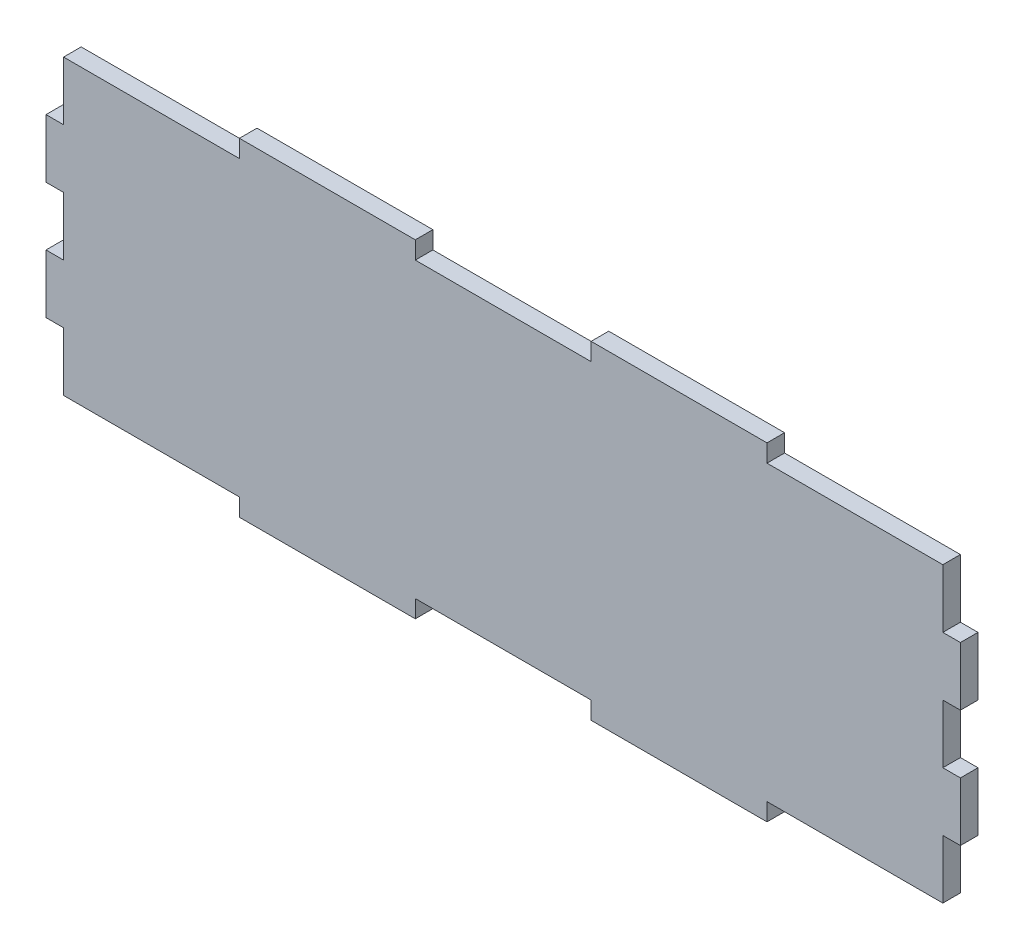
SolidWorks part; units mm, degrees
material "Pinho"
ref_plane "Plano frontal" through (0, 0, 0) normal (0, 0, 1) x (1, 0, 0)
ref_plane "Plano superior" through (0, 0, 0) normal (0, 1, 0) x (1, 0, 0)
ref_plane "Plano direito" through (0, 0, 0) normal (1, 0, 0) x (0, 0, -1)
sketch "Esboço1" plane through (0, 0, 0) normal (0, 0, 1) x (1, 0, 0)
  line L51 (-90, 33) -> (-90, 30)
  line L53 (-60, 30) -> (-60, 33)
  line L55 (-30, 33) -> (-30, 30)
  line L57 (0, 30) -> (0, 33)
  line L59 (-90, 33) -> (-60, 33)
  line L60 (-30, 33) -> (0, 33)
  line L62 (-60, 30) -> (-30, 30)
  line L65 (-90, -20) -> (-90, -23)
  line L66 (-90, -23) -> (-60, -23)
  line L67 (-60, -23) -> (-60, -20)
  line L68 (-60, -20) -> (-30, -20)
  line L69 (-30, -20) -> (-30, -23)
  line L82 (-90, -20) -> (-120, -20)
  line L83 (-120, -20) -> (-120, -10)
  line L84 (-120, -10) -> (-123, -10)
  line L85 (-123, -10) -> (-123, 0)
  line L86 (-123, 0) -> (-120, 0)
  line L87 (-120, 0) -> (-120, 10)
  line L88 (-120, 10) -> (-123, 10)
  line L89 (-123, 10) -> (-123, 20)
  line L90 (-123, 20) -> (-120, 20)
  line L91 (-120, 20) -> (-120, 30)
  line L92 (-120, 30) -> (-90, 30)
  line L93 (-30, -23) -> (0, -23)
  line L94 (0, -23) -> (0, -20)
  line L95 (0, -20) -> (30, -20)
  line L96 (30, -20) -> (30, -10)
  line L97 (30, -10) -> (33, -10)
  line L98 (33, -10) -> (33, 0)
  line L99 (33, 0) -> (30, 0)
  line L100 (30, 0) -> (30, 10)
  line L101 (30, 10) -> (33, 10)
  line L102 (33, 10) -> (33, 20)
  line L103 (33, 20) -> (30, 20)
  line L104 (30, 20) -> (30, 30)
  line L105 (30, 30) -> (0, 30)
  point P0 (0, 0)
  dimension "D1" = 150
  dimension "D2" = 10
  dimension "D3" = 10
  dimension "D4" = 30
  dimension "D5" = 50
  dimension "D6" = 3
  dimension "D7" = 3
  dimension "D8" = 3
extrude "Ressalto-extrusão1" add sketch "Esboço1" along normal blind 3
